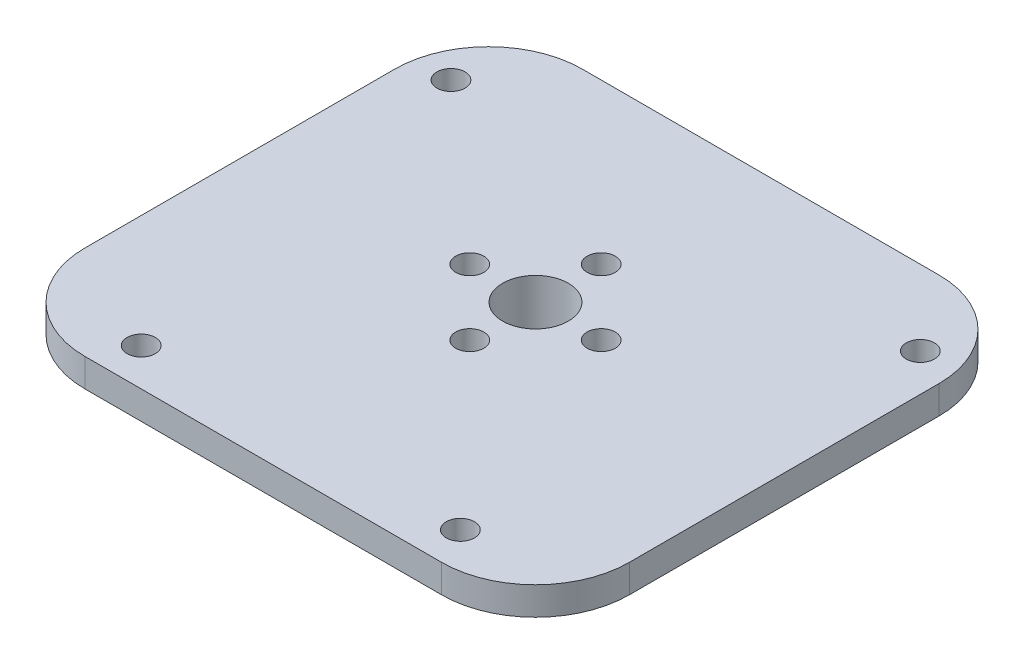
SolidWorks part; units mm, degrees
material "聚脂树脂"
ref_plane "前视基准面" through (0, 0, 0) normal (0, 0, 1) x (1, 0, 0)
ref_plane "上视基准面" through (0, 0, 0) normal (0, 1, 0) x (1, 0, 0)
ref_plane "右视基准面" through (0, 0, 0) normal (1, 0, 0) x (0, 0, -1)
other "Configuration Table"
sketch "草图1" plane through (0, 0, 0) normal (0, 1, 0) x (1, 0, 0)
  line L0 (0, 0) -> (36.9982, 0) construction
  line L1 (-29, -29) -> (29, -29)
  line L2 (-29, -29) -> (-29, 29)
  line L3 (-29, 29) -> (29, 29)
  line L4 (29, -29) -> (29, 29)
  line L5 (-29, -29) -> (29, 29) construction
  line L6 (-29, 29) -> (29, -29) construction
  line L7 (0, 0) -> (0, 22.4322) construction
  line L8 (0, 5) -> (42.8218, 5) construction
  circle A0 centre (0, 7) radius 1.5
  circle A1 centre (7, 0) radius 1.5
  circle A2 centre (0, 0) radius 3.5
  circle A3 centre (0, -7) radius 1.5
  circle A4 centre (-7, 0) radius 1.5
  circle A5 centre (25, 16) radius 1.5
  circle A11 centre (-25, 16) radius 1.5
  circle A12 centre (17, -25) radius 1.5
  circle A13 centre (-17, -25) radius 1.5
  point P0 (0, 0)
  dimension "D3" = 3
  dimension "D4" = 3
  dimension "D7" = 7
  dimension "D8" = 3
  dimension "D9" = 25
  dimension "D10" = 11
  dimension "D12" = 3
  dimension "D13" = 34
  dimension "D1" = 58
  dimension "D2" = 58
  dimension "D5" = 7
  dimension "D6" = 7
  dimension "D11" = 5
  dimension "D14" = 30
extrude "凸台-拉伸1" add sketch "草图1" along normal blind 3
sketch "草图2" plane through (0, 0, 0) normal (0, -1, 0) x (1, 0, 0)
  line L4 (29, -29) -> (29, 29)
  line L5 (29, 29) -> (-29, 29)
  line L6 (-29, 29) -> (-29, -29)
  line L7 (-29, -29) -> (29, -29)
  line L8 (29, -29) -> (29, 29)
  line L9 (29, 29) -> (-29, 29)
  line L10 (-29, 29) -> (-29, -29)
  line L11 (-29, -29) -> (29, -29)
  circle A0 centre (0, -7) radius 1.5 construction
  circle A1 centre (0, -7) radius 1.5
  circle A2 centre (-7, 0) radius 1.5 construction
  circle A3 centre (-7, 0) radius 1.5
  circle A4 centre (7, 0) radius 1.5 construction
  circle A5 centre (0, 7) radius 1.5 construction
  circle A6 centre (7, 0) radius 1.5
  circle A7 centre (0, 7) radius 1.5
  circle A8 centre (0, 0) radius 12.5
  circle A9 centre (0, 0) radius 3.5 construction
  circle A10 centre (0, 0) radius 3.5
  circle M6 centre (0, 7) radius 1.5
  circle M7 centre (7, 0) radius 1.5
  circle M12 centre (0, -7) radius 1.5
  circle M13 centre (0, 0) radius 3.5
  circle M14 centre (-7, 0) radius 1.5
  dimension "D2" = 25
  dimension "D1" = 0
extrude "凸台-拉伸2" add sketch "草图2" along normal blind 5 contours A8 M6 M13 M14 M12 M7
sketch "草图6" plane through (0, 0, 0) normal (0, -1, 0) x (1, 0, 0)
  circle A0 centre (0, 0) radius 12.5
  circle A1 centre (0, 0) radius 17
  dimension "D1" = 25
  dimension "D2" = 34
extrude "凸台-拉伸3" add sketch "草图6" along normal blind 7
sketch "草图8" plane through (0, 0, 0) normal (0, -1, 0) x (1, 0, 0)
  circle A0 centre (0, 0) radius 26
  circle A1 centre (0, 0) radius 12
  dimension "D1" = 24
  dimension "D2" = 52
extrude "凸台-拉伸5" add sketch "草图8" along normal blind 2
sketch "草图10" plane through (0, 3, 0) normal (0, 1, 0) x (1, 0, 0)
  line L0 (-29, 24) -> (-29, 29)
  line L1 (-29, 29) -> (-29, -29) construction
  line L2 (-29, 29) -> (29, 29)
  line L3 (29, 29) -> (29, 24)
  line L4 (29, -29) -> (29, 29) construction
  line L5 (29, 24) -> (-29, 24)
  dimension "D1" = 5
extrude "切除-拉伸1" cut sketch "草图10" against normal blind 10
fillet "圆角1" radius 10 4 edges at (-29, 1.5, 29) (29, 1.5, 29) (29, 1.5, -24) (-29, 1.5, -24)
